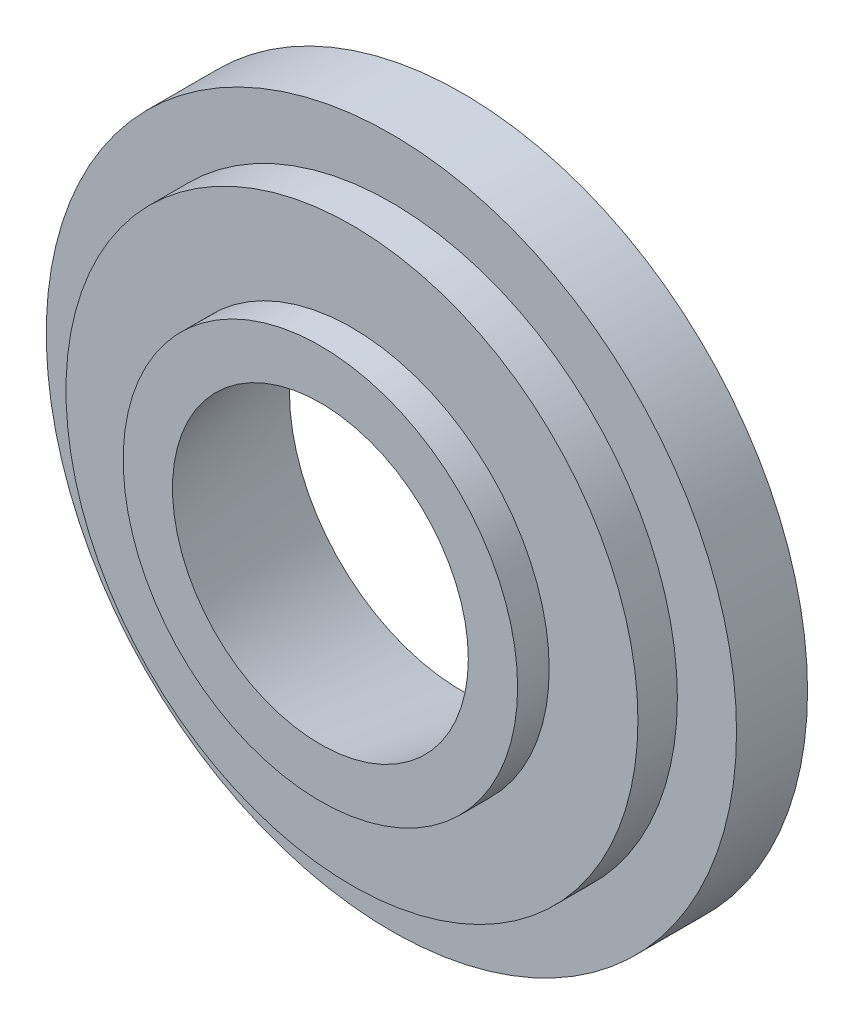
SolidWorks part; units mm, degrees
ref_plane "前视基准面" through (0, 0, 0) normal (0, 0, 1) x (1, 0, 0)
ref_plane "上视基准面" through (0, 0, 0) normal (0, 1, 0) x (1, 0, 0)
ref_plane "右视基准面" through (0, 0, 0) normal (1, 0, 0) x (0, 0, -1)
sketch "草图1" plane through (0, 0, 0) normal (0, 0, 1) x (1, 0, 0)
  circle A0 centre (0, 0) radius 87.5
  dimension "D1" = 175
extrude "凸台-拉伸1" add sketch "草图1" along normal blind 18
sketch "草图2" plane through (0, 0, 18) normal (0, 0, 1) x (1, 0, 0)
  circle A0 centre (0, 0) radius 72.5
  dimension "D1" = 145
extrude "凸台-拉伸2" add sketch "草图2" along normal blind 10
sketch "草图3" plane through (0, 0, 28) normal (0, 0, 1) x (1, 0, 0)
  circle A0 centre (0, 0) radius 50
  dimension "D1" = 100
extrude "凸台-拉伸3" add sketch "草图3" along normal blind 8
sketch "草图4" plane through (0, 0, 0) normal (0, 0, -1) x (-1, 0, 0)
  circle A0 centre (0, 0) radius 60.5
  circle A1 centre (0, 0) radius 51.5
  dimension "D1" = 121
  dimension "D2" = 103
extrude "切除-拉伸1" cut sketch "草图4" against normal blind 5
sketch "草图5" plane through (0, 0, 36) normal (0, 0, 1) x (1, 0, 0)
  circle A0 centre (0, 0) radius 37.5
  dimension "D1" = 75
extrude "切除-拉伸2" cut sketch "草图5" against normal through all draft 10 draft outward yes
ref_plane "基准面1" through (0, 0, 6) normal (0, 0, -1) x (-1, 0, 0)
ref_plane "基准面2" through (0, 0, 30) normal (0, 0, 1) x (1, 0, 0)
sketch3d "3D草图1"
  circle A2 centre (0, 0, 30) radius 38.558
  circle A3 centre (0, 0, 30) radius 38.558
  point P7 (0, 0, 68.558)
  point P9 (0, 0, 68.558)
